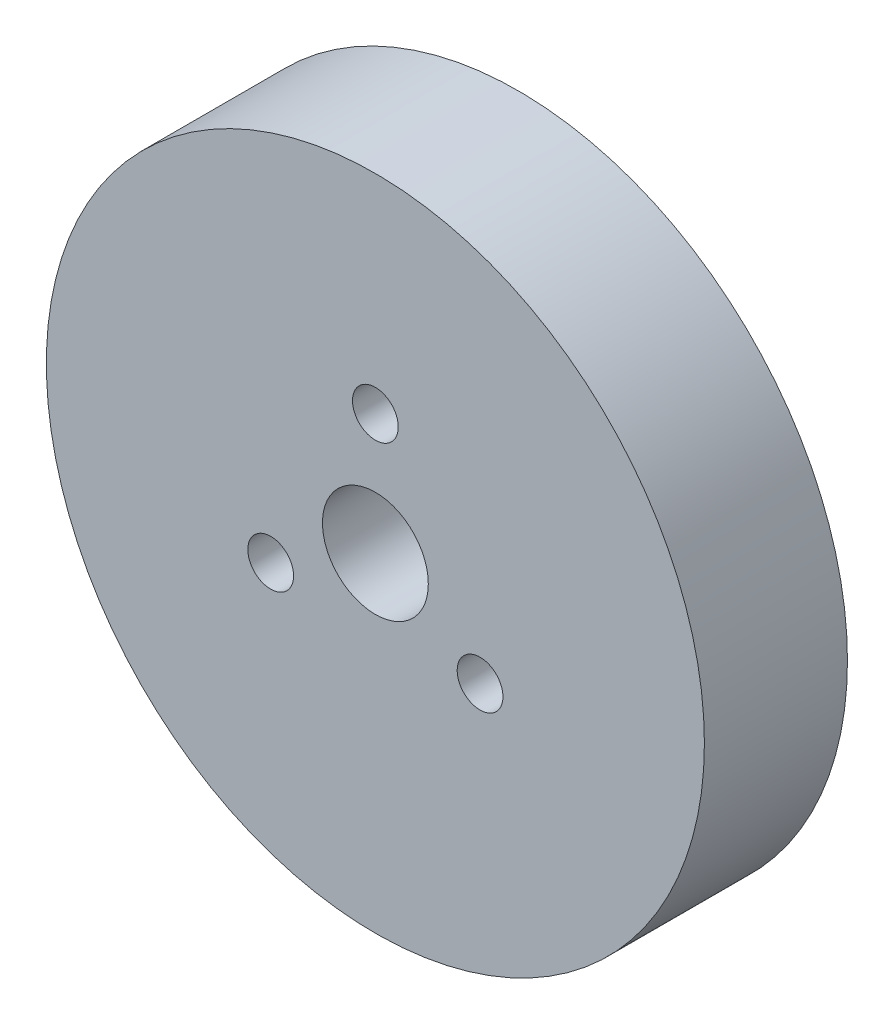
SolidWorks part; units mm, degrees
other "Rim-Inside" parameters "D1"=11.4465, "D2"=30.9038, "D3"=3.4737, "D4"=12.1609
ref_plane "Front Plane" through (0, 0, 0) normal (0, 0, 1) x (1, 0, 0)
ref_plane "Top Plane" through (0, 0, 0) normal (0, 1, 0) x (1, 0, 0)
ref_plane "Right Plane" through (0, 0, 0) normal (1, 0, 0) x (0, 0, -1)
sketch "Sketch1" plane through (0, 0, 0) normal (0, 0, 1) x (1, 0, 0)
  circle A0 centre (0, 0) radius 3.7
  circle A1 centre (0, 0) radius 23
  circle A5 centre (0, 0) radius 18
  dimension "D1" = 7.4
  dimension "D2" = 46
  dimension "D4" = 36
extrude "Boss-Extrude1" add sketch "Sketch1" along normal blind 10
sketch "Sketch6" plane through (0, 0, 0) normal (0, 0, -1) x (-1, 0, 0)
  line L0 (0, 0) -> (0, 8.45) construction
  line L1 (0, 0) -> (7.3179, -4.225) construction
  line L2 (0, 0) -> (-7.3179, -4.225) construction
  dimension "D2" = 8.45
  dimension "D1" = 3
hole_wizard "Hole1" positions "3DSketch2" profile "Sketch8" legacy
sketch3d "3DSketch2"
  point P0 (0, 8.45, 0)
  point P3 (7.3179, -4.225, 0)
  point P6 (-7.3179, -4.225, 0)
sketch "Sketch8" plane through (0, 8.45, 0) normal (1, 0, 0) x (0, 1, 0)
  line L0 (0, 0) -> (0, 9.999)
  line L1 (0, 9.999) -> (1.6, 9.999)
  line L2 (1.6, 9.999) -> (1.6, 0)
  line L3 (1.6, 0) -> (0, 0)
  line L4 (0, 110) -> (0, -10) construction
  dimension "Diameter" = 3.2
  dimension "Depth" = 9.999
equation "\"M3 Nut Diameter\" = 5.50mm"
equation "\"Clearance Diameter 3D Printing\" = .20mm"
equation "\"D-Shaft\"= 4mm'D-Shaft diameter"
equation "\"Wheel Axle Diameter\"= 6.8mm'Axle to Connect to Wheel"
equation "\"Wheel Thickness\"= 10mm'Wheel Thickness"
equation "\"M3 Screw Diameter\"= 3.20mm'M3 Screw Diameter already with 3D printing Clearance"
equation "\"D1@Sketch1\" = \"Wheel Axle Diameter\" + .6mm"
equation "\"Wheel Diameter\"= 60mm"
equation "\"Silicone Tire Width\"= 7mm"
equation "\"D2@Sketch1\"= \"Wheel Diameter\" - 2 * \"Silicone Tire Width\""
equation "\"D2@Sketch6\"= ( \"Wheel Axle Diameter\" / 2 ) + ( ( \"M3 Nut Diameter\" + \"Clearance Diameter 3D Printing\" + .40mm ) / 2 ) + 2mm"
equation "\"D1@Boss-Extrude1\"=10mm"
equation "\"Diameter\"= \"M3 Screw Diameter\""
equation "\"Logo Diameter\"= 36mm"
equation "\"D4@Sketch1\"= \"Logo Diameter\""
